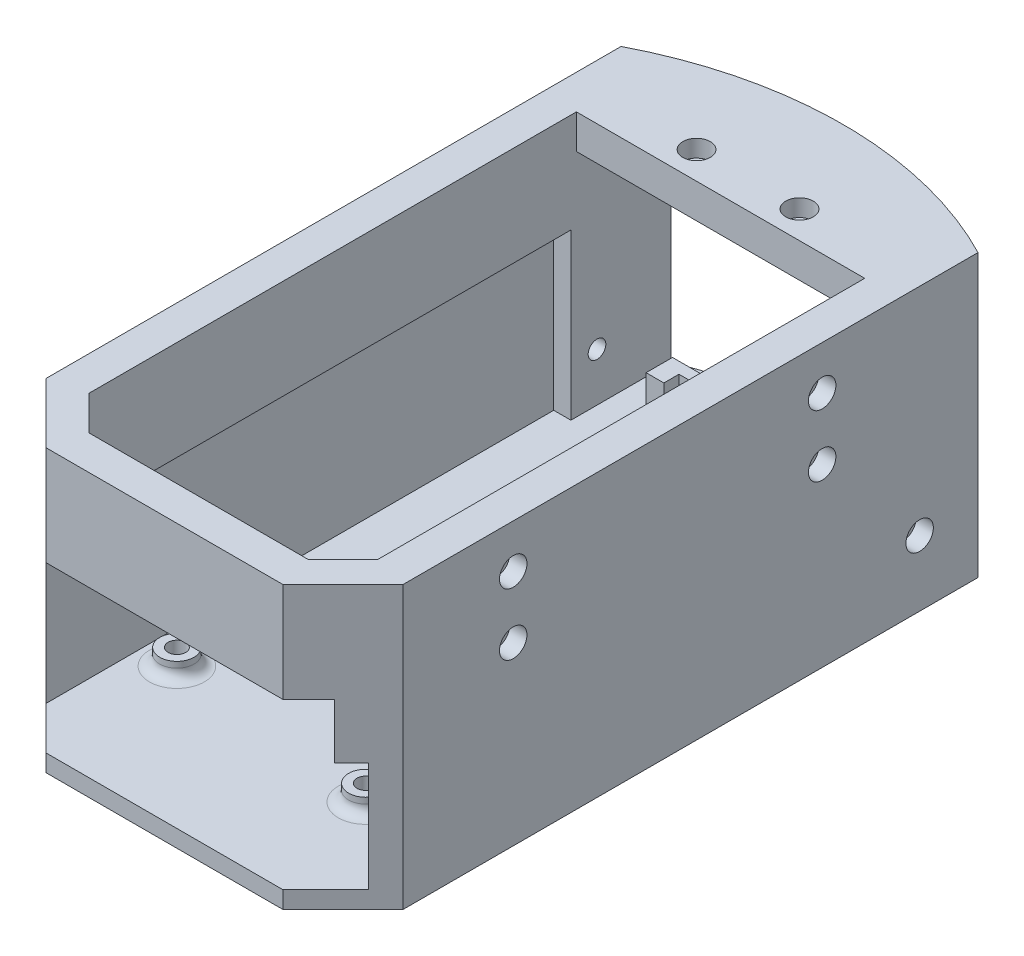
SolidWorks part; units mm, degrees
ref_plane "Front Plane" through (0, 0, 0) normal (0, 0, 1) x (1, 0, 0)
ref_plane "Top Plane" through (0, 0, 0) normal (0, 1, 0) x (1, 0, 0)
ref_plane "Right Plane" through (0, 0, 0) normal (1, 0, 0) x (0, 0, -1)
sketch "Sketch1" plane through (0, 0, 0) normal (0, 0, 1) x (1, 0, 0)
  line L0 (0, 12.2587) -> (0, -12.2587) construction
  line L1 (-26.67, 19.685) -> (26.67, 19.685)
  line L2 (-26.67, 19.685) -> (-26.67, -22.86)
  line L3 (-26.67, -22.86) -> (26.67, -22.86)
  line L4 (26.67, 19.685) -> (26.67, -22.86)
  line L5 (-33.02, 26.035) -> (33.02, 26.035)
  line L6 (-33.02, 26.035) -> (-33.02, -26.035)
  line L7 (-33.02, -26.035) -> (33.02, -26.035)
  line L8 (33.02, 26.035) -> (33.02, -26.035)
  line L9 (-17.9084, 0) -> (16.6292, 0) construction
  dimension "D1" = 6.35
  dimension "D2" = 6.35
  dimension "D3" = 52.07
  dimension "D4" = 66.04
  dimension "D5" = 3.175
extrude "Boss-Extrude1" add sketch "Sketch1" along normal blind 152.4
sketch "Sketch3" plane through (0, 26.035, 0) normal (0, 1, 0) x (1, 0, 0)
  line L0 (0, 0) -> (0, -140.0152) construction
  line L1 (-26.67, -22.6568) -> (26.67, -22.6568)
  line L2 (-26.67, -22.6568) -> (-26.67, -152.4)
  line L3 (-26.67, -152.4) -> (26.67, -152.4)
  line L4 (26.67, -22.6568) -> (26.67, -152.4)
  line L5 (33.02, 0) -> (-33.02, 0) construction
  line L6 (26.67, -152.4) -> (26.67, 0) construction
  line L7 (33.02, -152.4) -> (-33.02, -152.4) construction
  dimension "D2" = 22.6568
extrude "Cut-Extrude2" cut sketch "Sketch3" against normal up to surface (48.895 mm away) up to face at (0, -22.86, 76.2)
sketch "Sketch5" plane through (0, 26.035, 0) normal (0, 1, 0) x (1, 0, 0)
  line L0 (26.67, -152.4) -> (26.67, -22.6568) construction
  line L1 (26.67, -119.1768) -> (-26.67, -119.1768)
  line L2 (26.67, -119.1768) -> (26.67, -152.4)
  line L3 (26.67, -152.4) -> (-26.67, -152.4)
  line L4 (-26.67, -119.1768) -> (-26.67, -152.4)
  line L5 (-26.67, -22.6568) -> (-26.67, -152.4) construction
  line L6 (26.67, -22.6568) -> (-26.67, -22.6568) construction
  line L7 (-26.67, -152.4) -> (26.67, -152.4) construction
  line L8 (26.67, -119.1768) -> (26.67, -112.8268)
  line L9 (26.67, -112.8268) -> (20.32, -119.1768)
  line L10 (0, 0) -> (0, -219.9236) construction
  line L11 (33.02, 0) -> (-33.02, 0) construction
  line L12 (-26.67, -112.8268) -> (-20.32, -119.1768)
  line L13 (-26.67, -119.1768) -> (-26.67, -112.8268)
  line L14 (-26.67, -112.8268) -> (-26.67, -119.1768)
  line L15 (-26.67, -119.1768) -> (-20.32, -119.1768)
  line L16 (26.67, -112.8268) -> (26.67, -119.1768)
  line L17 (26.67, -119.1768) -> (26.675, -119.2097)
  line M13 (-26.67, -152.4) -> (-26.67, -22.6568)
  line M14 (26.67, -22.6568) -> (26.67, -152.4)
  dimension "D1" = 96.52
  dimension "D2" = 45
  dimension "D3" = 6.35
extrude "Boss-Extrude3" add sketch "Sketch5" against normal up to vertex (48.895 mm away) contours L9 L1 M14 | L12 L1 M13 | L10 L1 L3 M13 | L1 L10 L3 M14
sketch "Sketch6" plane through (0, 26.035, 0) normal (0, 1, 0) x (1, 0, 0)
  line L0 (44.5827, -125.5268) -> (-44.5827, -125.5268)
  line L1 (-86.109, 31.1462) -> (91.691, 31.1462)
  line L2 (-86.109, 31.1462) -> (-86.109, -172.0538)
  line L3 (-86.109, -172.0538) -> (91.691, -172.0538)
  line L4 (91.691, 31.1462) -> (91.691, -172.0538)
  line L5 (33.02, 0) -> (-33.02, 0) construction
  line L6 (-43.18, -16.8504) -> (-44.3576, -15.353)
  line L7 (43.18, -16.8504) -> (44.3576, -15.353)
  line L8 (20.32, -119.1768) -> (-20.32, -119.1768) construction
  line L10 (0, 14.7539) -> (0, -99.5316) construction
  line L11 (-33.02, -152.4) -> (-33.02, 0) construction
  line L12 (33.02, -152.4) -> (33.02, 0) construction
  arc A0 (-43.18, -16.8504) -> (-44.5827, -125.5268) centre (0, -71.755) ccw
  arc A1 (44.3576, -15.353) -> (-44.3576, -15.353) centre (0, -71.755) ccw
  arc A2 (44.5827, -125.5268) -> (43.18, -16.8504) centre (0, -71.755) ccw
  dimension "D1" = 139.7
  dimension "D4" = 143.51
  dimension "D2" = 203.2
  dimension "D3" = 177.8
  dimension "D5" = 6.35
  dimension "D6" = 10.16
  dimension "D7" = 10.16
extrude "Cut-Extrude3" cut sketch "Sketch6" against normal through all
hole_wizard "#4 Clearance Hole3" positions "Sketch10" profile "Sketch9" hole size "#4" standard "ANSI Inch"
sketch "Sketch10" plane through (0, 26.035, 0) normal (0, 1, 0) x (1, 0, 0)
  line L0 (0, -6.9666) -> (0, -42.3625) construction
  line L2 (26.67, -22.6568) -> (-26.67, -22.6568) construction
  point P0 (-9.525, -17.5768)
  point P2 (9.525, -17.5768)
  dimension "D1" = 19.05
  dimension "D2" = 5.08
sketch "Sketch9" plane through (-9.525, 26.035, 17.5768) normal (1, 0, 0) x (0, 0, 1)
  line L0 (0, 0) -> (0, 6.35)
  line L1 (0, 6.35) -> (1.6319, 6.35)
  line L2 (1.6319, 6.35) -> (1.6319, 0)
  line L5 (1.6319, 0) -> (0, 0)
  line L11 (0, -6.35) -> (0, 107.95) construction
  dimension "Thru Hole Dia." = 3.2639
  dimension "Thru Hole Depth" = 6.35
sketch "Sketch12" plane through (0, 26.035, 0) normal (0, 1, 0) x (1, 0, 0)
  circle A0 centre (-9.525, -17.5768) radius 2.54
  circle A1 centre (9.525, -17.5768) radius 2.54
  dimension "D1" = 5.08
  dimension "D2" = 5.08
extrude "Cut-Extrude5" cut sketch "Sketch12" against normal blind 3.175
hole_wizard "#4 Clearance Hole4" positions "Sketch14" profile "Sketch13" hole size "#4" standard "ANSI Inch"
sketch "Sketch14" plane through (-26.67, 0, 0) normal (1, 0, 0) x (0, 0, -1)
  line L0 (-112.8268, -22.86) -> (-5.1405, -22.86) construction
  line L1 (-5.1405, -22.86) -> (-5.1405, 19.685) construction
  point P0 (-18.8468, -13.9065)
  dimension "D1" = 8.9535
  dimension "D2" = 13.7063
sketch "Sketch13" plane through (-26.67, -13.9065, 18.8468) normal (0, 1, 0) x (0, 0, -1)
  line L0 (0, 0) -> (0, 13.6806)
  line L1 (0, 13.6806) -> (1.6319, 12.7)
  line L2 (1.6319, 12.7) -> (1.6319, 0)
  line L5 (1.6319, 0) -> (0, 0)
  line L10 (0, 13.6806) -> (-1.632, 12.7) construction
  line L11 (0, -6.35) -> (0, 107.95) construction
  dimension "Hole Dia." = 3.2639
  dimension "Hole Depth" = 12.7
  dimension "Drill Angle" = 118
sketch "Sketch15" plane through (-33.02, 0, 0) normal (-1, 0, 0) x (0, 0, 1)
  circle A0 centre (18.8468, -13.9065) radius 2.54
  dimension "D1" = 5.08
extrude "Cut-Extrude6" cut sketch "Sketch15" against normal blind 3.175
mirror "Mirror1" about plane through (0, 0, 0) normal (1, 0, 0) of "#4 Clearance Hole4", "Cut-Extrude6"
sketch "Sketch16" plane through (0, 0, 125.5268) normal (0, 0, -1) x (-1, 0, 0)
  line L0 (-33.02, 26.035) -> (-33.02, -26.035) construction
  line L1 (-26.67, 7.62) -> (29.845, 7.62)
  line L2 (-29.845, -2.54) -> (-29.845, -22.86)
  line L3 (-29.845, -22.86) -> (29.845, -22.86)
  line L4 (29.845, 7.62) -> (29.845, -22.86)
  line L5 (33.02, -26.035) -> (33.02, 26.035) construction
  line L6 (26.67, -22.86) -> (-26.67, -22.86) construction
  line L7 (-26.67, 19.685) -> (-26.67, -22.86) construction
  line L9 (-26.67, 7.62) -> (-26.67, -2.54)
  line L10 (-26.67, -2.54) -> (-29.845, -2.54)
  dimension "D1" = 3.175
  dimension "D2" = 3.175
  dimension "D3" = 30.48
  dimension "D4" = 10.16
extrude "Cut-Extrude9" cut sketch "Sketch16" along normal blind 101.854 contours L1 L4 L3 L2 L10 L9
sketch "Sketch18" plane through (0, -22.86, 0) normal (0, 1, 0) x (1, 0, 0)
  line L0 (0, 21.2879) -> (0, -164.2458) construction
  line L1 (-13.335, -23.0988) -> (16.383, -23.0988)
  line L2 (-13.335, -23.0988) -> (-13.335, -18.2118)
  line L3 (-13.335, -18.2118) -> (16.383, -18.2118)
  line L4 (16.383, -23.0988) -> (16.383, -18.2118)
  line L6 (26.67, -22.6568) -> (-26.67, -22.6568) construction
  line L7 (29.845, -125.5268) -> (29.845, -23.6728) construction
  line L8 (-29.845, -125.5268) -> (-29.845, -23.6728) construction
  dimension "D1" = 13.462
  dimension "D2" = 4.887
  dimension "D3" = 4.445
  dimension "D4" = 16.51
extrude "SD card holder" add sketch "Sketch18" along normal blind 13.9954
sketch "Sketch19" plane through (0, 0, 23.0988) normal (0, 0, 1) x (1, 0, 0)
  line L0 (-13.335, -8.8646) -> (16.383, -8.8646) construction
  line L1 (14.2875, -8.8646) -> (-10.0457, -8.8646)
  line L2 (14.2875, -8.8646) -> (14.2875, -14.5034)
  line L3 (14.2875, -14.5034) -> (-10.0457, -14.5034)
  line L4 (-10.0457, -8.8646) -> (-10.0457, -14.5034)
  line L5 (-13.335, -22.86) -> (16.383, -22.86) construction
  line L6 (-13.335, -8.8646) -> (-13.335, -22.86) construction
  dimension "D1" = 24.3332
  dimension "D2" = 3.2893
  dimension "D3" = 8.3566
extrude "Cut-Extrude10" cut sketch "Sketch19" against normal blind 2.794
sketch "Sketch30" plane through (0, -14.5034, 0) normal (0, 1, 0) x (1, 0, 0)
  line L1 (-10.0457, -20.3048) -> (-7.5057, -20.3048)
  line L2 (-10.0457, -20.3048) -> (-10.0457, -22.5908)
  line L3 (-10.0457, -22.5908) -> (-7.5057, -22.5908)
  line L4 (-7.5057, -20.3048) -> (-7.5057, -22.5908)
  line L5 (14.2875, -20.3048) -> (11.7475, -20.3048)
  line L6 (14.2875, -20.3048) -> (14.2875, -22.5908)
  line L7 (14.2875, -22.5908) -> (11.7475, -22.5908)
  line L8 (11.7475, -20.3048) -> (11.7475, -22.5908)
  dimension "D1" = 2.286
  dimension "D2" = 2.54
extrude "Boss-Extrude7" [suppressed] add sketch "Sketch30" along normal blind 4.191
sketch "Sketch20" plane through (0, -22.86, 0) normal (0, 1, 0) x (1, 0, 0)
  circle A0 centre (-9.8819, -49.2038) radius 3.175
  circle A1 centre (15.5181, -103.8138) radius 3.175
  circle A2 centre (-23.7249, -99.5085) radius 3.175
  circle A3 centre (-9.8819, -49.2038) radius 1.45 construction
  circle A4 centre (15.5181, -103.8138) radius 1.45 construction
  circle A5 centre (-23.7249, -99.5085) radius 1.45 construction
  dimension "D2" = 6.35
extrude "mount post " add sketch "Sketch20" along normal blind 3
hole_wizard "#4 Clearance Hole1" positions "Sketch22" profile "Sketch21" hole size "#4" standard "ANSI Inch" end condition up to next
sketch "Sketch22" plane through (0, -19.86, 0) normal (0, 1, 0) x (1, 0, 0)
  circle A0 centre (-9.8819, -49.2038) radius 3.175 construction
  circle A1 centre (15.5181, -103.8138) radius 3.175 construction
  point P2 (15.5181, -103.8138)
  point P7 (-9.8819, -49.2038)
  point P17 (-23.7249, -99.5085)
sketch "Sketch21" plane through (15.5181, -19.86, 103.8138) normal (1, 0, 0) x (0, 0, 1)
  line L0 (0, 0) -> (0, 6.175)
  line L1 (0, 6.175) -> (1.6319, 6.175)
  line L2 (1.6319, 6.175) -> (1.6319, 0)
  line L5 (1.6319, 0) -> (0, 0)
  line L11 (0, -6.35) -> (0, 107.95) construction
  dimension "Thru Hole Dia." = 3.2639
  dimension "Thru Hole Depth" = 6.175
sketch "Sketch23" plane through (0, -26.035, 0) normal (0, -1, 0) x (1, 0, 0)
  line L1 (-7.1542, 49.2038) -> (-8.5181, 51.566)
  line L2 (-8.5181, 51.566) -> (-11.2457, 51.566)
  line L3 (-11.2457, 51.566) -> (-12.6095, 49.2038)
  line L4 (-12.6095, 49.2038) -> (-11.2457, 46.8416)
  line L5 (-11.2457, 46.8416) -> (-8.5181, 46.8416)
  line L6 (-8.5181, 46.8416) -> (-7.1542, 49.2038)
  line L7 (18.2458, 103.8138) -> (16.8819, 106.176)
  line L8 (16.8819, 106.176) -> (14.1543, 106.176)
  line L9 (14.1543, 106.176) -> (12.7905, 103.8138)
  line L10 (12.7905, 103.8138) -> (14.1543, 101.4516)
  line L11 (14.1543, 101.4516) -> (16.8819, 101.4516)
  line L12 (16.8819, 101.4516) -> (18.2458, 103.8138)
  line L13 (-22.3611, 97.1463) -> (-20.9972, 99.5085)
  line L14 (-20.9972, 99.5085) -> (-22.3611, 101.8707)
  line L15 (-22.3611, 101.8707) -> (-25.0887, 101.8707)
  line L16 (-25.0887, 101.8707) -> (-26.4525, 99.5085)
  line L17 (-26.4525, 99.5085) -> (-25.0887, 97.1463)
  line L18 (-25.0887, 97.1463) -> (-22.3611, 97.1463)
  circle A0 centre (-9.8819, 49.2038) radius 2.3622 construction
  circle A1 centre (15.5181, 103.8138) radius 2.3622 construction
  circle A2 centre (-23.7249, 99.5085) radius 2.3622 construction
  dimension "D1" = 4.7244
extrude "Cut-Extrude11" cut sketch "Sketch23" against normal blind 1.905
sketch "Sketch24" plane through (0, 0, 125.5268) normal (0, 0, -1) x (-1, 0, 0)
  line L0 (-33.02, 26.035) -> (33.02, 26.035) construction
  line L1 (-26.67, 3.175) -> (-20.32, 3.175)
  line L2 (-26.67, 3.175) -> (-26.67, 9.525)
  line L3 (-26.67, 9.525) -> (-20.32, 9.525)
  line L4 (-20.32, 3.175) -> (-20.32, 9.525)
  line L6 (-26.67, 7.62) -> (-26.67, 26.035) construction
  dimension "D1" = 6.35
  dimension "D2" = 6.35
  dimension "D3" = 16.51
extrude "Cut-Extrude12" [suppressed] cut sketch "Sketch24" along normal up to next
hole_wizard "#4 Clearance Hole2" positions "Sketch26" profile "Sketch25" hole size "#4" standard "ANSI Inch"
sketch "Sketch26" plane through (33.02, 0, 0) normal (1, 0, 0) x (0, 0, -1)
  line L1 (-125.5268, 26.035) -> (-8.049, 26.035) construction
  point P0 (-94.0308, 17.9388)
  point P2 (-94.0308, 6.5088)
  point P4 (-36.8808, 17.9388)
  point P6 (-36.8808, 6.5088)
  dimension "D1" = 11.43
  dimension "D2" = 57.15
  dimension "D3" = 14.224
  dimension "D4" = 8.0962
sketch "Sketch25" plane through (33.02, 17.9388, 94.0308) normal (0, 1, 0) x (0, 0, -1)
  line L0 (0, 0) -> (0, 6.35)
  line L1 (0, 6.35) -> (1.6319, 6.35)
  line L2 (1.6319, 6.35) -> (1.6319, 0)
  line L5 (1.6319, 0) -> (0, 0)
  line L11 (0, -6.35) -> (0, 107.95) construction
  dimension "Thru Hole Dia." = 3.2639
  dimension "Thru Hole Depth" = 6.35
sketch "Sketch27" plane through (33.02, 0, 0) normal (1, 0, 0) x (0, 0, -1)
  circle A0 centre (-94.0308, 17.9388) radius 2.54
  circle A1 centre (-94.0308, 6.5088) radius 2.54
  circle A2 centre (-36.8808, 17.9388) radius 2.54
  circle A3 centre (-36.8808, 6.5088) radius 2.54
  dimension "D4" = 5.08
extrude "Cut-Extrude13" cut sketch "Sketch27" against normal blind 3.175
fillet "Fillet1" radius 1.905 3 edges at (-13.335, -22.86, 20.6553) (1.524, -22.86, 18.2118) (16.383, -22.86, 20.6553)
fillet "Fillet2" radius 1.905 3 edges at (12.3431, -22.86, 103.8138) (-13.0569, -22.86, 49.2038) (-26.8999, -22.86, 99.5085)
sketch3d "3DSketch2"
  line L1 (-44.9013, 89.535, 19.9302) -> (44.9013, 89.535, 109.7328)
  line L2 (-44.9013, 89.535, 19.9302) -> (-44.9013, -37.465, 19.9302)
  line L3 (-44.9013, -37.465, 19.9302) -> (44.9013, -37.465, 109.7328)
  line L4 (44.9013, 89.535, 109.7328) -> (44.9013, -37.465, 109.7328)
  line L5 (-44.9013, 89.535, 19.9302) -> (44.9013, -37.465, 109.7328) construction
  line L6 (-44.9013, -37.465, 19.9302) -> (44.9013, 89.535, 109.7328) construction
  line L7 (-44.9013, 89.535, 109.7328) -> (-44.9013, -37.465, 109.7328)
  line L8 (-44.9013, 89.535, 109.7328) -> (44.9013, 89.535, 19.9302)
  line L9 (44.9013, 89.535, 19.9302) -> (44.9013, -37.465, 19.9302)
  line L10 (-44.9013, -37.465, 109.7328) -> (44.9013, -37.465, 19.9302)
  line L11 (-44.9013, 89.535, 109.7328) -> (44.9013, -37.465, 19.9302) construction
  line L12 (44.9013, 89.535, 19.9302) -> (-44.9013, -37.465, 109.7328) construction
  line L13 (0, 26.035, 154.6341) -> (89.8026, 26.035, 64.8315)
  line L14 (0, 26.035, 154.6341) -> (-89.8026, 26.035, 64.8315)
  line L15 (-89.8026, 26.035, 64.8315) -> (0, 26.035, -24.971)
  line L16 (89.8026, 26.035, 64.8315) -> (0, 26.035, -24.971)
  line L17 (0, 26.035, 154.6341) -> (0, 26.035, -24.971) construction
  line L18 (-89.8026, 26.035, 64.8315) -> (89.8026, 26.035, 64.8315) construction
  point P0 (-4.2104, 12.1793, 5.6296)
  point P6 (0, 26.035, 64.8315)
  point P11 (0, 0, 0)
  point P16 (0, 26.035, 64.8315)
  dimension "D1" = 127
  dimension "D2" = 127
  dimension "D3" = 127
  dimension "D4" = 127
  dimension "D5" = 127
  dimension "D6" = 127
sketch "Sketch28" plane through (0, 26.035, 0) normal (0, 1, 0) x (1, 0, 0)
  line L0 (40.4112, -107.0387) -> (0, -147.4499)
  line L1 (0, -154.6341) -> (0, 24.971) construction
  line L2 (0, -147.4499) -> (-40.4112, -107.0387)
  line L3 (-40.4112, -107.0387) -> (-54.7796, -121.4071)
  line L4 (-54.7796, -121.4071) -> (0, -176.1867)
  line L5 (0, -176.1867) -> (54.7796, -121.4071)
  line L6 (54.7796, -121.4071) -> (40.4112, -107.0387)
  line L7 (0, -154.6341) -> (89.8026, -64.8315) construction
  dimension "D1" = 5.08
  dimension "D2" = 20.32
  dimension "D3" = 20.32
  dimension "D4" = 57.15
  dimension "D5" = 57.15
extrude "Cut-Extrude15" cut sketch "Sketch28" against normal up to next
sketch "Sketch31" plane through (0, 0, 125.5268) normal (0, 0, 1) x (1, 0, 0)
  line L0 (0, 0) -> (0, -26.035) construction
  line L1 (-21.9231, -26.035) -> (21.9231, -26.035) construction
  line L3 (-3.175, -26.035) -> (3.175, -26.035)
  line L4 (-3.175, -26.035) -> (-3.175, -31.115)
  line L5 (-3.175, -31.115) -> (3.175, -31.115)
  line L6 (3.175, -26.035) -> (3.175, -31.115)
  line L7 (-3.175, -27.94) -> (-6.35, -27.94)
  line L8 (-3.175, -27.94) -> (-3.175, -31.115)
  line L9 (-3.175, -31.115) -> (-6.35, -31.115)
  line L10 (-6.35, -27.94) -> (-6.35, -31.115)
  line L11 (3.175, -27.94) -> (6.35, -27.94)
  line L12 (3.175, -27.94) -> (3.175, -31.115)
  line L13 (3.175, -31.115) -> (6.35, -31.115)
  line L14 (6.35, -27.94) -> (6.35, -31.115)
  dimension "D1" = 5.08
  dimension "D2" = 3.175
  dimension "D3" = 6.35
  dimension "D4" = 3.175
extrude "Boss-Extrude8" add sketch "Sketch31" against normal blind 107.95
fillet "Fillet3" radius 1.27 8 edges at (-6.35, -31.115, 71.5518) (-6.35, -29.5275, 125.5268) (-6.35, -29.5275, 17.5768) (-6.35, -27.94, 71.5518) (6.35, -27.94, 71.5518) (6.35, -29.5275, 125.5268) (6.35, -29.5275, 17.5768) (6.35, -31.115, 71.5518)
sketch "Sketch32" plane through (-33.02, 0, 0) normal (-1, 0, 0) x (0, 0, 1)
  line L1 (125.5268, -26.035) -> (87.4268, -26.035)
  line L2 (125.5268, -26.035) -> (125.5268, -32.385)
  line L3 (125.5268, -32.385) -> (87.4268, -32.385)
  line L4 (87.4268, -26.035) -> (87.4268, -32.385)
  dimension "D1" = 38.1
  dimension "D2" = 6.35
extrude "Cut-Extrude16" cut sketch "Sketch32" against normal through all
